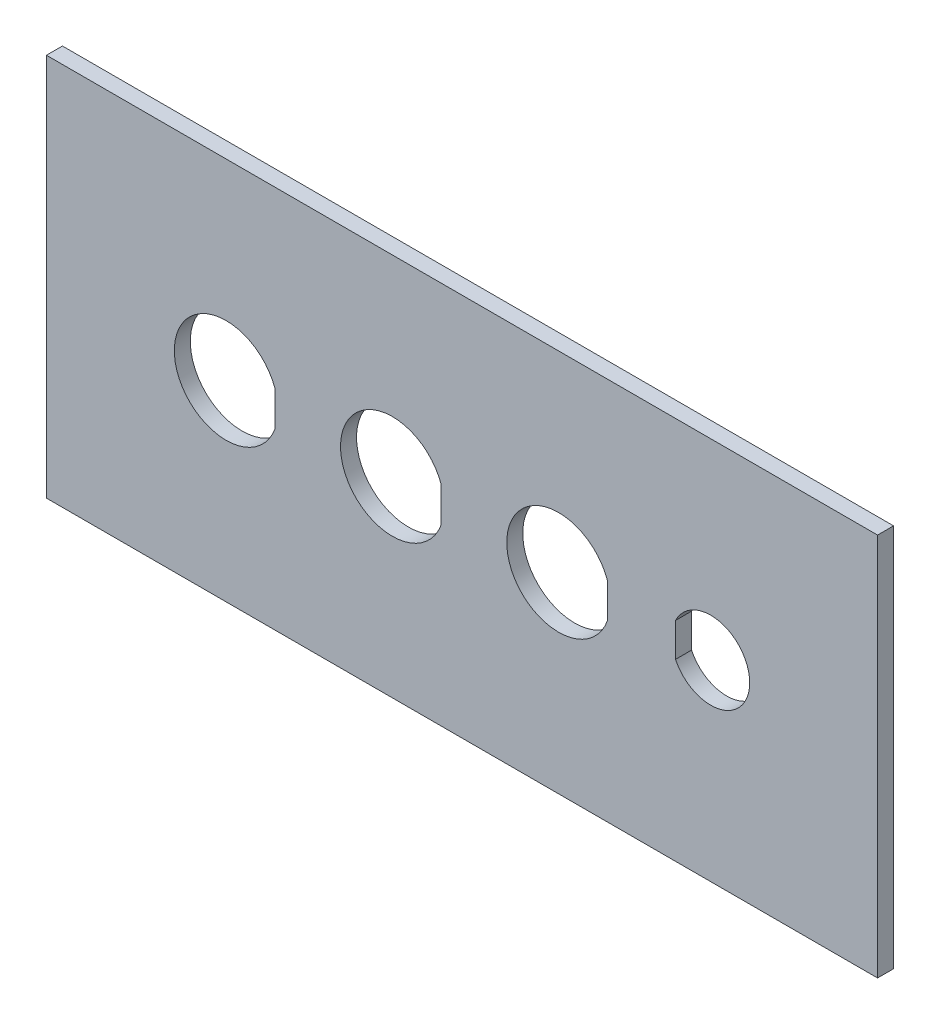
SolidWorks part; units mm, degrees
ref_plane "Front Plane" through (0, 0, 0) normal (0, 0, 1) x (1, 0, 0)
ref_plane "Top Plane" through (0, 0, 0) normal (0, 1, 0) x (1, 0, 0)
ref_plane "Right Plane" through (0, 0, 0) normal (1, 0, 0) x (0, 0, -1)
sketch "Sketch1" plane through (0, 0, 0) normal (0, 0, 1) x (1, 0, 0)
  line L1 (-73.1988, 37.6067) -> (91.9012, 37.6067)
  line L2 (-73.1988, 37.6067) -> (-73.1988, -38.5933)
  line L3 (-73.1988, -38.5933) -> (91.9012, -38.5933)
  line L4 (91.9012, 37.6067) -> (91.9012, -38.5933)
  line L5 (-73.1988, 37.6067) -> (91.9012, -38.5933) construction
  line L6 (-73.1988, -38.5933) -> (91.9012, 37.6067) construction
  line L8 (-73.1988, -0.4933) -> (91.9012, -0.4933) construction
  line L12 (51.7692, 2.8571) -> (51.7692, -3.8438)
  line L13 (-27.7988, 2.9708) -> (-27.7988, -3.9574)
  line L14 (5.2212, 2.9708) -> (5.2212, -3.9574)
  line L15 (38.2412, 2.9708) -> (38.2412, -3.9574)
  arc A6 (51.7692, -3.8438) -> (51.7692, 2.8571) centre (58.7542, -0.4933) ccw
  arc A7 (-27.7988, 2.9708) -> (-27.7988, -3.9574) centre (-37.4988, -0.4933) ccw
  arc A8 (5.2212, 2.9708) -> (5.2212, -3.9574) centre (-4.4788, -0.4933) ccw
  arc A9 (38.2412, 2.9708) -> (38.2412, -3.9574) centre (28.5412, -0.4933) ccw
  point P5 (66.5012, -0.4933)
  point P10 (0, 0)
  point P11 (-47.7988, -0.4933)
  point P12 (0, 0)
  dimension "D3" = 14.732
  dimension "D6" = 25.4
  dimension "D4" = 15.494
  dimension "D5" = 20.6
  dimension "D1" = 165.1
  dimension "D2" = 76.2
  dimension "D7" = 25.4
  dimension "D8" = 20
  dimension "D9" = 3
extrude "Boss-Extrude1" add sketch "Sketch1" along normal blind 3.175
